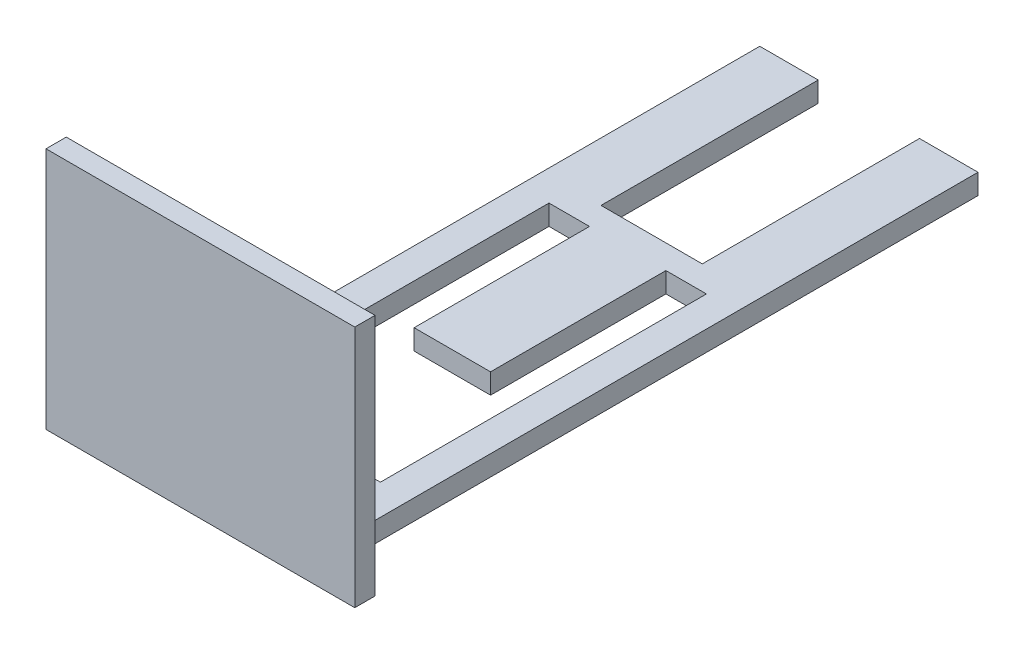
SolidWorks part; units mm, degrees
ref_plane "Front Plane" through (0, 0, 0) normal (0, 0, 1) x (1, 0, 0)
ref_plane "Top Plane" through (0, 0, 0) normal (0, 1, 0) x (1, 0, 0)
ref_plane "Right Plane" through (0, 0, 0) normal (1, 0, 0) x (0, 0, -1)
ref_plane "Plane1" through (6.6595, 0, 0) normal (1, 0, 0) x (0, 0, -1)
sketch "Sketch1" plane through (6.6595, 0, 0) normal (1, 0, 0) x (0, 0, -1)
  line L0 (-2.2509, -1) -> (-2.9669, -1)
  line L1 (-2.9669, -1) -> (-2.9669, -2.3486)
  line L2 (-2.9669, -2.3486) -> (-2.2509, -1)
extrude "Boss-Extrude1" add sketch "Sketch1" against normal blind 5.7724
sketch "Sketch2" plane through (0, -1, 0) normal (0, 1, 0) x (-1, 0, 0)
  line L0 (-0.8871, 2.9669) -> (-0.8871, 9.404)
  line L1 (-0.8871, 9.404) -> (-8.6595, 9.404)
  line L2 (-8.6595, 9.404) -> (-8.6595, -6.6904)
  line L3 (-8.6595, -6.6904) -> (-6.6595, -6.6904)
  line L4 (-6.6595, -6.6904) -> (-6.6595, 2.9669)
  line L5 (-6.6595, 2.9669) -> (-0.8871, 2.9669)
  line L6 (0.6129, -18.596) -> (-10.1595, -18.596)
  line L7 (-10.1595, -18.596) -> (-10.1595, 14.404)
  line L8 (-10.1595, 14.404) -> (0.6129, 14.404)
  line L9 (0.6129, 14.404) -> (0.6129, -18.596)
extrude "Boss-Extrude2" add sketch "Sketch2" along normal blind 1
ref_plane "Plane2" through (0.8871, 0, 0) normal (-1, 0, 0) x (0, 0, 1)
sketch "Sketch7" plane through (0.8871, 0, 0) normal (-1, 0, 0) x (0, 0, 1)
  line L0 (2.2509, -1) -> (2.9669, -2.3486)
  line L1 (2.9669, -2.3486) -> (2.9669, 0)
  line L2 (2.9669, 0) -> (-6.6904, 0)
  line L3 (-6.6904, 0) -> (-6.6904, -1)
  line L4 (-6.6904, -1) -> (2.2509, -1)
extrude "Cut-Extrude1" cut sketch "Sketch7" against normal blind 2
ref_plane "Plane3" through (0, 0, 2.9669) normal (0, 0, 1) x (1, 0, 0)
sketch "Sketch13" plane through (0, 0, 2.9669) normal (0, 0, 1) x (1, 0, 0)
  line L0 (6.6595, 0) -> (6.6595, -2.3486)
  line L1 (6.6595, -2.3486) -> (2.8871, -2.3486)
  line L2 (2.8871, -2.3486) -> (2.8871, 0)
  line L3 (2.8871, 0) -> (6.6595, 0)
sketch "Sketch16" plane through (0, 0, 0) normal (0, 1, 0) x (1, 0, 0)
  line L0 (-0.6129, -13.404) -> (10.1595, -13.404)
  line L1 (10.1595, -13.404) -> (10.1595, -14.404)
  line L2 (10.1595, -14.404) -> (-0.6129, -14.404)
  line L3 (-0.6129, -14.404) -> (-0.6129, -13.404)
extrude "Boss-Extrude4" add sketch "Sketch16" along normal blind 11
ref_plane "Plane4" through (2.8871, 0, 0) normal (-1, 0, 0) x (0, 0, 1)
sketch "Sketch23" plane through (2.8871, 0, 0) normal (-1, 0, 0) x (0, 0, 1)
  line L0 (2.2509, 0) -> (2.2509, -0.1259)
  line L1 (2.2509, -0.1259) -> (3.1223, -1.8357)
  line L2 (3.1223, -1.8357) -> (3.713, -1.8357)
  line L3 (3.713, -1.8357) -> (3.713, 0)
  line L4 (3.713, 0) -> (2.2509, 0)
extrude "Cut-Extrude2" cut sketch "Sketch23" against normal up to next
sketch "Sketch26" plane through (0, 0, 0) normal (0, 1, 0) x (1, 0, 0)
  line L0 (7.2721, 18.596) -> (2.2721, 18.596)
  line L1 (2.2721, 18.596) -> (2.2721, 7.8738)
  line L2 (2.2721, 7.8738) -> (7.2721, 7.8738)
  line L3 (7.2721, 7.8738) -> (7.2721, 18.596)
extrude "Cut-Extrude3" cut sketch "Sketch26" against normal through all
extrude "Cut-Extrude4" cut sketch "Sketch13" against normal blind 1 contours L3 L0 L1 L2
sketch "Sketch27" plane through (-0.6129, 0, 0) normal (-1, 0, 0) x (0, 0, 1)
  line L1 (13.404, 11) -> (14.404, 11)
  line L2 (13.404, 11) -> (13.404, -1)
  line L3 (13.404, -1) -> (14.404, -1)
  line L4 (14.404, 11) -> (14.404, -1)
extrude "Boss-Extrude5" add sketch "Sketch27" along normal blind 2.235
sketch "Sketch28" plane through (10.1595, 0, 0) normal (1, 0, 0) x (0, 0, -1)
  line L1 (-14.404, 11) -> (-13.404, 11)
  line L2 (-14.404, 11) -> (-14.404, -1)
  line L3 (-14.404, -1) -> (-13.404, -1)
  line L4 (-13.404, 11) -> (-13.404, -1)
extrude "Boss-Extrude6" add sketch "Sketch28" along normal blind 2.235
